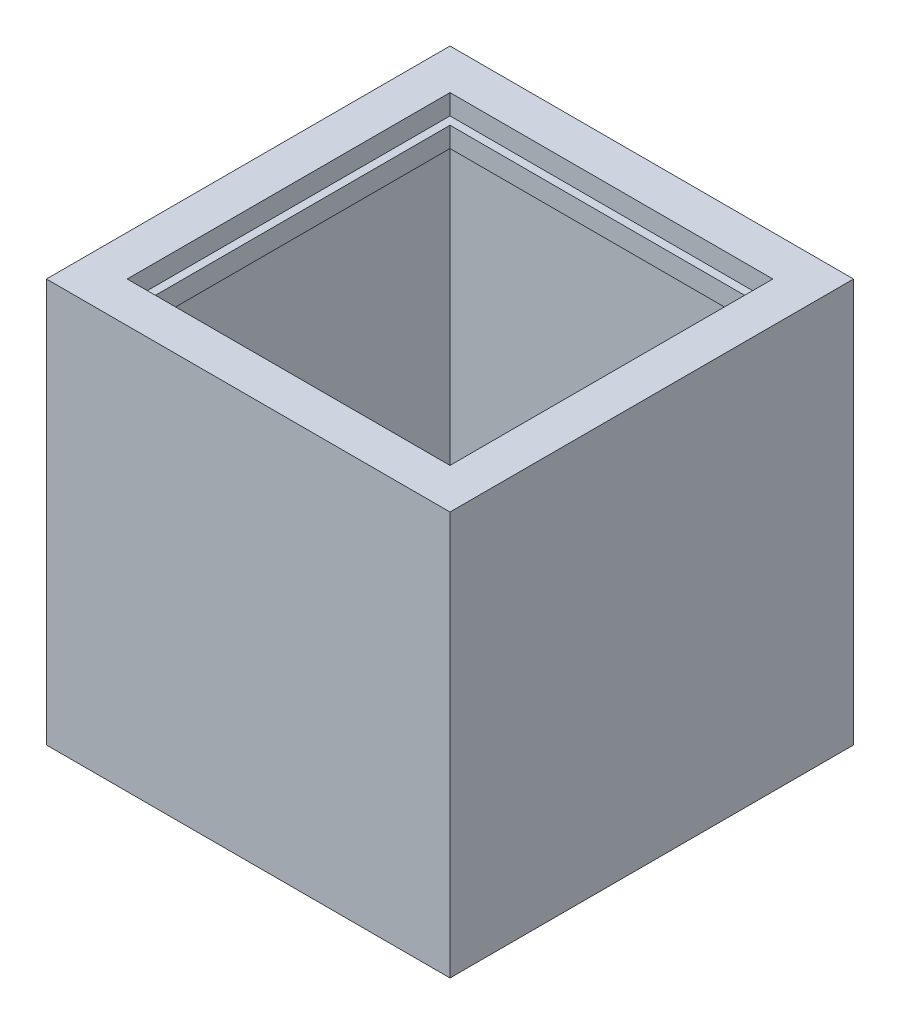
SolidWorks part; units mm, degrees
ref_plane "Front Plane" through (0, 0, 0) normal (0, 0, 1) x (1, 0, 0)
ref_plane "Top Plane" through (0, 0, 0) normal (0, 1, 0) x (1, 0, 0)
ref_plane "Right Plane" through (0, 0, 0) normal (1, 0, 0) x (0, 0, -1)
sketch "Sketch1" plane through (0, 0, 0) normal (0, 0, 1) x (1, 0, 0)
  line L1 (-63.5, -63.5) -> (63.5, -63.5)
  line L2 (-63.5, -63.5) -> (-63.5, 63.5)
  line L3 (-63.5, 63.5) -> (63.5, 63.5)
  line L4 (63.5, -63.5) -> (63.5, 63.5)
  line L5 (-63.5, -63.5) -> (63.5, 63.5) construction
  line L6 (-63.5, 63.5) -> (63.5, -63.5) construction
  point P0 (0, 0)
  dimension "D1" = 127
  dimension "D2" = 127
extrude "Boss-Extrude1" add sketch "Sketch1" along normal blind 127
sketch "Sketch2" plane through (0, 63.5, 0) normal (0, 1, 0) x (1, 0, 0)
  line L16 (-48.26, -15.24) -> (-48.26, -111.76)
  line L17 (-48.26, -111.76) -> (48.26, -111.76)
  line L18 (48.26, -111.76) -> (48.26, -15.24)
  line L19 (48.26, -15.24) -> (-48.26, -15.24)
  line L20 (-48.26, -15.24) -> (-48.26, -111.76)
  line L21 (-48.26, -111.76) -> (48.26, -111.76)
  line L22 (48.26, -111.76) -> (48.26, -15.24)
  line L23 (48.26, -15.24) -> (-48.26, -15.24)
  dimension "D1" = 15.24
extrude "Cut-Extrude1" cut sketch "Sketch2" against normal blind 118.11
sketch "Sketch3" plane through (0, 63.5, 0) normal (0, 1, 0) x (1, 0, 0)
  line L1 (-48.26, -15.24) -> (48.26, -15.24)
  line L2 (-48.26, -15.24) -> (-48.26, -111.76)
  line L3 (-48.26, -111.76) -> (48.26, -111.76)
  line L4 (48.26, -15.24) -> (48.26, -111.76)
  line L14 (-50.8, -114.3) -> (50.8, -114.3)
  line L15 (50.8, -114.3) -> (50.8, -12.7)
  line L16 (-50.8, -12.7) -> (-50.8, -114.3)
  line L17 (50.8, -12.7) -> (-50.8, -12.7)
  line L18 (-50.8, -114.3) -> (50.8, -114.3)
  line L19 (50.8, -114.3) -> (50.8, -12.7)
  line L20 (-50.8, -12.7) -> (-50.8, -114.3)
  line L21 (50.8, -12.7) -> (-50.8, -12.7)
  dimension "D1" = 2.54
extrude "Cut-Extrude2" cut sketch "Sketch3" against normal blind 6.35
sketch "Sketch5" plane through (0, 0, 15.24) normal (0, 0, 1) x (1, 0, 0)
  line L0 (-48.26, -54.61) -> (-48.26, 57.15) construction
  line L1 (-48.26, 50.8) -> (48.26, 50.8)
  line L2 (-48.26, 50.8) -> (-48.26, -54.61)
  line L3 (-48.26, -54.61) -> (48.26, -54.61)
  line L4 (48.26, 50.8) -> (48.26, -54.61)
  line L5 (48.26, -54.61) -> (-48.26, -54.61) construction
  line L6 (48.26, -54.61) -> (48.26, 57.15) construction
  line L7 (50.8, 57.15) -> (-50.8, 57.15) construction
  dimension "D1" = 6.35
extrude "Cut-Extrude3" cut sketch "Sketch5" against normal blind 6.35
ref_plane "Plane1" through (0, 0, 63.5) normal (0, 0, -1) x (-1, 0, 0)
mirror "Mirror1" about plane through (0, 0, 63.5) normal (0, 0, -1) of "Cut-Extrude3"
sketch "Sketch6" plane through (48.26, 0, 0) normal (-1, 0, 0) x (0, 0, 1)
  line L0 (118.11, -54.61) -> (118.11, 50.8) construction
  line L1 (8.89, -54.61) -> (118.11, -54.61)
  line L2 (8.89, -54.61) -> (8.89, 50.8)
  line L3 (8.89, 50.8) -> (118.11, 50.8)
  line L4 (118.11, -54.61) -> (118.11, 50.8)
  line L5 (8.89, 50.8) -> (15.24, 50.8) construction
  dimension "D1" = 0
extrude "Cut-Extrude4" cut sketch "Sketch6" against normal blind 6.35
mirror "Mirror2" about plane through (0, 0, 0) normal (1, 0, 0) of "Cut-Extrude4"
